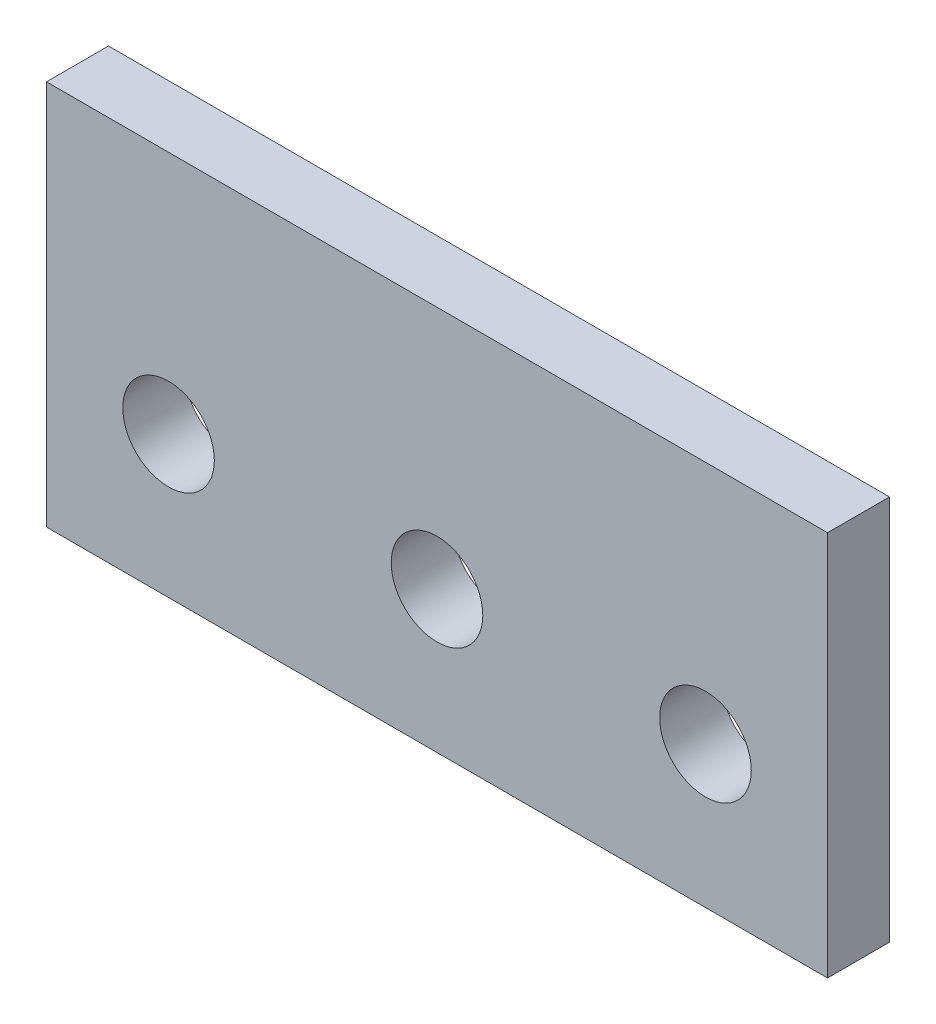
SolidWorks part; units mm, degrees
ref_plane "Alzado" through (0, 0, 0) normal (0, 0, 1) x (1, 0, 0)
ref_plane "Planta" through (0, 0, 0) normal (0, 1, 0) x (1, 0, 0)
ref_plane "Vista lateral" through (0, 0, 0) normal (1, 0, 0) x (0, 0, -1)
sketch "Croquis1" plane through (0, 0, 0) normal (0, 0, 1) x (1, 0, 0)
  line L0 (-160, -58) -> (160, -58)
  line L2 (-160, -58) -> (-160, 100)
  line L3 (-160, 100) -> (160, 100)
  line L4 (160, -58) -> (160, 100)
  line L5 (-92.8, -58) -> (160, 100) construction
  line L6 (-160, 100) -> (92.8, -58) construction
  circle A0 centre (0, 0) radius 18.7647
  circle A1 centre (110, 0) radius 18.7647
  circle A2 centre (-110, 0) radius 18.7647
  point P0 (0, 0)
  dimension "D2" = 110
  dimension "D5" = 110
  dimension "D1" = 158
  dimension "D3" = 2
  dimension "D4" = 2
extrude "Saliente-Extruir1" add sketch "Croquis1" along normal blind 25.4
